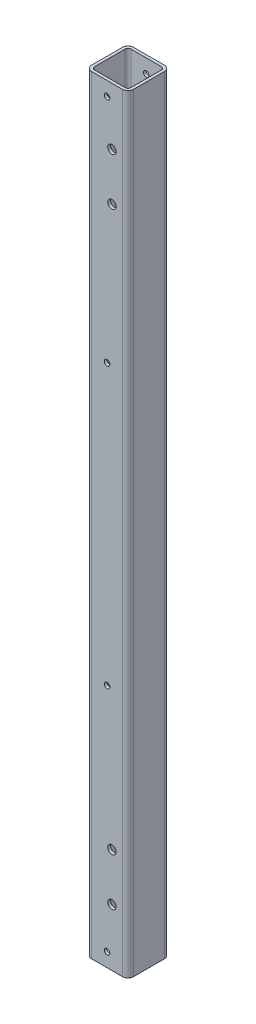
SolidWorks part; units mm, degrees
material "AISI 1010 钢，热轧条材"
ref_plane "前视基准面" through (0, 0, 0) normal (0, 0, 1) x (1, 0, 0)
ref_plane "上视基准面" through (0, 0, 0) normal (0, 1, 0) x (1, 0, 0)
ref_plane "右视基准面" through (0, 0, 0) normal (1, 0, 0) x (0, 0, -1)
sketch "草图1" plane through (0, 0, 0) normal (0, 1, 0) x (1, 0, 0)
  line L0 (4, 2) -> (26, 2)
  line L1 (4, 0) -> (26, 0)
  line L2 (0, 4) -> (0, 26)
  line L3 (4, 30) -> (26, 30)
  line L4 (30, 4) -> (30, 26)
  line L5 (28, 4) -> (28, 26)
  line L6 (4, 28) -> (26, 28)
  line L7 (2, 4) -> (2, 26)
  arc A0 (4, 0) -> (0, 4) centre (4, 4) cw
  arc A1 (26, 0) -> (30, 4) centre (26, 4) ccw
  arc A2 (26, 30) -> (30, 26) centre (26, 26) cw
  arc A3 (0, 26) -> (4, 30) centre (4, 26) cw
  arc A4 (26, 2) -> (28, 4) centre (26, 4) ccw
  arc A5 (26, 28) -> (28, 26) centre (26, 26) cw
  arc A6 (2, 26) -> (4, 28) centre (4, 26) cw
  arc A7 (4, 2) -> (2, 4) centre (4, 4) cw
  point P7 (0, 0)
  point P10 (30, 0)
  point P13 (30, 30)
  point P16 (0, 30)
  dimension "D3" = 4
  dimension "D1" = 30
  dimension "D2" = 30
  dimension "D4" = 2
extrude "凸台-拉伸1" add sketch "草图1" along normal mid plane 550
sketch "草图2" plane through (0, 0, 0) normal (0, 0, 1) x (1, 0, 0)
  line L0 (0, 0) -> (30, 0) construction
  line L1 (30, 275) -> (30, -275) construction
  line L2 (0, 275) -> (0, -275) construction
  line L4 (4, 275) -> (26, 275) construction
  circle A0 centre (18.5, 234) radius 3
  circle A1 centre (18.5, 200) radius 3
  circle A2 centre (18.5, -200) radius 3
  circle A3 centre (18.5, -234) radius 3
  circle A4 centre (15, 265) radius 2
  circle A5 centre (15, 100) radius 2
  circle A6 centre (15, -100) radius 2
  circle A7 centre (15, -265) radius 2
  dimension "D4" = 6
  dimension "D5" = 4
  dimension "D1" = 200
  dimension "D2" = 34
  dimension "D3" = 18.5
  dimension "D6" = 15
  dimension "D7" = 10
  dimension "D8" = 100
extrude "切除-拉伸1" cut sketch "草图2" against normal through all
